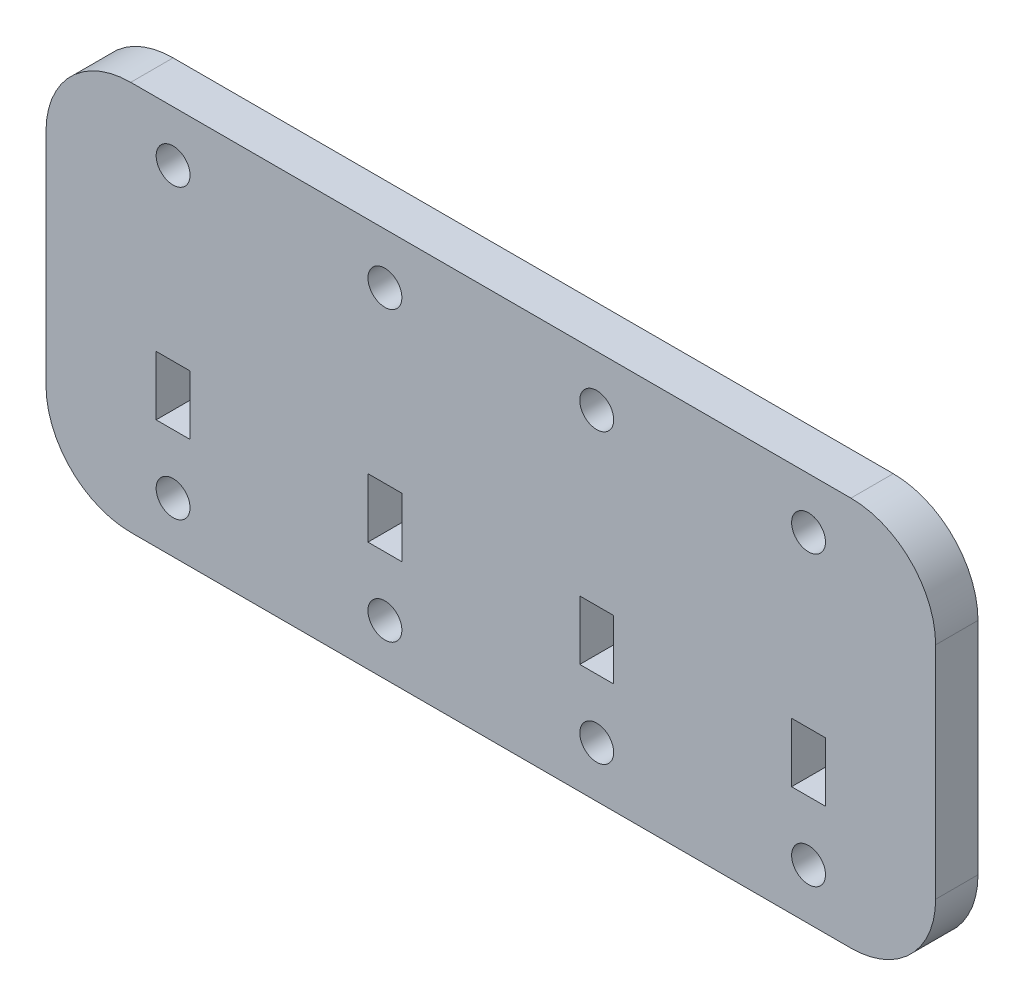
SolidWorks part; units mm, degrees
ref_plane "Plan de face" through (0, 0, 0) normal (0, 0, 1) x (1, 0, 0)
ref_plane "Plan de dessus" through (0, 0, 0) normal (0, 1, 0) x (1, 0, 0)
ref_plane "Plan de droite" through (0, 0, 0) normal (1, 0, 0) x (0, 0, -1)
sketch "Esquisse1" plane through (0, 0, 0) normal (0, 0, 1) x (1, 0, 0)
  line L0 (0, 40) -> (105, 40) construction
  line L1 (0, 0) -> (105, 0)
  line L2 (0, 0) -> (0, 46)
  line L3 (0, 46) -> (105, 46)
  line L4 (105, 0) -> (105, 46)
  line L5 (105, 6) -> (0, 6) construction
  line L6 (15, 40) -> (15, 6) construction
  line L7 (42, 20) -> (42, 13)
  line L8 (13, 20) -> (17, 20)
  line L9 (13, 20) -> (13, 13)
  line L10 (13, 13) -> (17, 13)
  line L11 (17, 20) -> (17, 13)
  line L12 (38, 13) -> (42, 13)
  line L13 (38, 20) -> (38, 13)
  line L14 (38, 20) -> (42, 20)
  line L15 (67, 20) -> (67, 13)
  line L16 (63, 13) -> (67, 13)
  line L17 (63, 20) -> (63, 13)
  line L18 (63, 20) -> (67, 20)
  line L19 (92, 20) -> (92, 13)
  line L20 (88, 13) -> (92, 13)
  line L21 (88, 20) -> (88, 13)
  line L22 (88, 20) -> (92, 20)
  circle A0 centre (15, 6) radius 2
  circle A1 centre (15, 40) radius 2
  circle A2 centre (40, 40) radius 2
  circle A3 centre (40, 6) radius 2
  circle A4 centre (65, 40) radius 2
  circle A5 centre (65, 6) radius 2
  circle A6 centre (90, 40) radius 2
  circle A7 centre (90, 6) radius 2
  dimension "D4" = 4
  dimension "D6" = 4
  dimension "D1" = 34
  dimension "D2" = 6
  dimension "D3" = 6
  dimension "D5" = 15
  dimension "D7" = 25
  dimension "D8" = 15
  dimension "D9" = 7
  dimension "D10" = 20
  dimension "D11" = 4
  dimension "D12" = 4
  dimension "D14" = 25
  dimension "D13" = 4
extrude "Boss.-Extru.1" add sketch "Esquisse1" along normal blind 5
fillet "Congé1" radius 10 4 edges at (0, 0, 2.5) (105, 0, 2.5) (105, 46, 2.5) (0, 46, 2.5)
